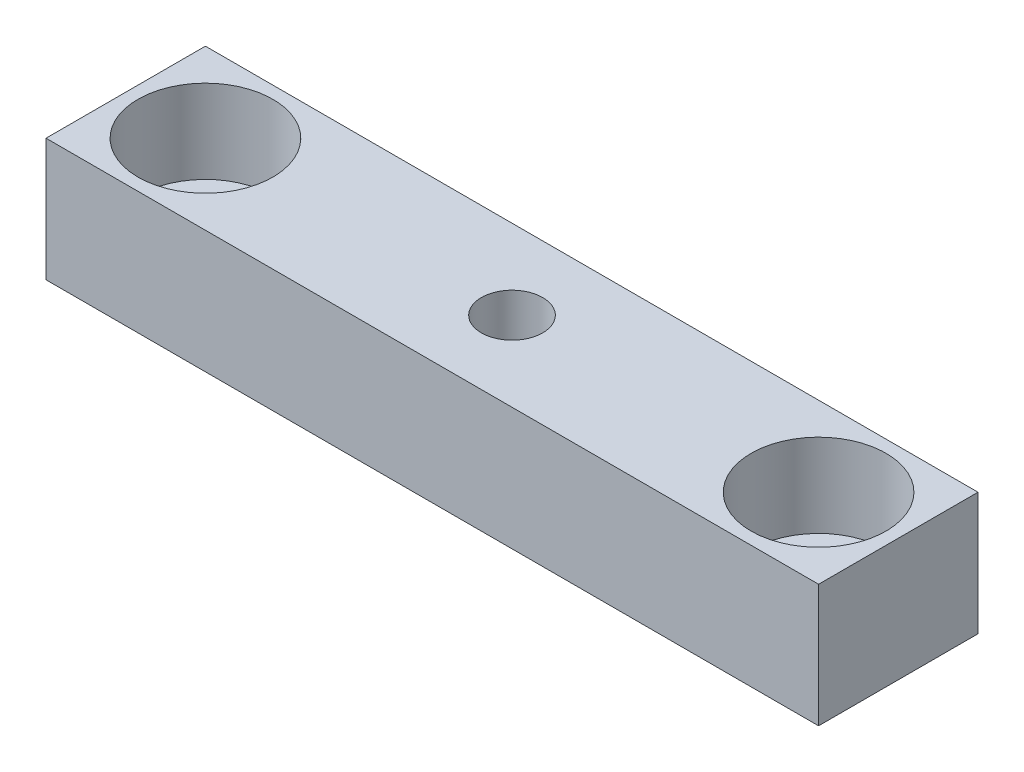
SolidWorks part; units mm, degrees
material "6061 合金"
ref_plane "前视基准面" through (0, 0, 0) normal (0, 0, 1) x (1, 0, 0)
ref_plane "上视基准面" through (0, 0, 0) normal (0, 1, 0) x (1, 0, 0)
ref_plane "右视基准面" through (0, 0, 0) normal (1, 0, 0) x (0, 0, -1)
sketch "草图1" plane through (0, 0, 0) normal (0, 1, 0) x (1, 0, 0)
  line L1 (-31.5, 6.5) -> (31.5, 6.5)
  line L2 (-31.5, 6.5) -> (-31.5, -6.5)
  line L3 (-31.5, -6.5) -> (31.5, -6.5)
  line L4 (31.5, 6.5) -> (31.5, -6.5)
  line L5 (-31.5, 6.5) -> (31.5, -6.5) construction
  line L6 (-31.5, -6.5) -> (31.5, 6.5) construction
  point P0 (0, 0)
extrude "凸台-拉伸1" add sketch "草图1" along normal blind 10
sketch "草图2" plane through (0, 10, 0) normal (0, 1, 0) x (1, 0, 0)
  line L0 (-25, 0) -> (25, 0) construction
  line L1 (-16.5, 0) -> (16.5, 0) construction
  point P6 (0, 0)
hole_wizard "打孔尺寸(%根据)内六角圆柱头螺钉的类型1" positions "3D草图1" profile "草图3" counterbore size "M6" standard "GB" end condition through all
sketch3d "3D草图1"
  point P0 (-25, 10, 0)
  point P3 (25, 10, 0)
sketch "草图3" plane through (-25, 10, 0) normal (1, 0, 0) x (0, 0, 1)
  line L0 (0, 0) -> (0, 10)
  line L1 (0, 10) -> (3.3, 10)
  line L3 (3.3, 10) -> (3.3, 6.8)
  line L4 (3.3, 6.8) -> (5.5, 6.8)
  line L5 (5.5, 6.8) -> (5.5, 0)
  line L7 (5.5, 0) -> (0, 0)
  line L11 (0, -6.35) -> (0, 107.95) construction
  dimension "通孔孔直径" = 6.6
  dimension "通孔孔深度" = 10
  dimension "柱形沉头孔直径" = 11
  dimension "柱形沉头孔深度" = 6.8
sketch "草图4" plane through (0, 0, 0) normal (0, -1, 0) x (1, 0, 0)
  line L0 (-25, 0) -> (-15, 0) construction
  line L1 (-25, 0) -> (25, 0) construction
  line L2 (25, 0) -> (15, 0) construction
  dimension "D1" = 10
  dimension "D2" = 10
hole_wizard "大小mm 暗销孔1" positions "3D草图2" profile "草图5" hole size "Ø4.0" standard "GB"
sketch3d "3D草图2"
  point P0 (-15, 0, 0)
sketch "草图5" plane through (-15, 0, 0) normal (1, 0, 0) x (0, 0, -1)
  line L0 (0, 0) -> (0, 6.2017)
  line L1 (0, 6.2017) -> (2, 5)
  line L2 (2, 5) -> (2, 0)
  line L5 (2, 0) -> (0, 0)
  line L10 (0, 6.2017) -> (-2, 5) construction
  line L11 (0, -6.35) -> (0, 107.95) construction
  dimension "孔直径" = 4
  dimension "孔深度" = 5
  dimension "导头角度" = 118
sketch "草图6" plane through (0, 0, 0) normal (0, -1, 0) x (1, 0, 0)
  line L0 (14.5, 0) -> (15.5, 0) construction
  line L1 (-25, 0) -> (25, 0) construction
  line L2 (14.5, 2) -> (15.5, 2)
  line L3 (14.5, -2) -> (15.5, -2)
  arc A0 (14.5, 2) -> (14.5, -2) centre (14.5, 0) ccw
  arc A1 (15.5, -2) -> (15.5, 2) centre (15.5, 0) ccw
  circle A2 centre (-15, 0) radius 2 construction
  point P5 (15, 0)
  dimension "D1" = 1
extrude "切除-拉伸1" cut sketch "草图6" against normal blind 5
fillet "圆角1" [suppressed] radius 2
sketch "草图7" plane through (0, 0, 0) normal (0, 1, 0) x (1, 0, 0)
  circle A0 centre (0, 0) radius 2
hole_wizard "M6 螺纹孔1" positions "3D草图3" profile "草图8" tap size "M6" standard "GB" end condition through all
sketch3d "3D草图3"
  circle A0 centre (0, 0, 0) radius 2 construction
  point P0 (0, 0, 0)
  point P3 (0, 0, 0)
  point P5 (0, 0, 0)
  point P11 (0, 2, 0)
sketch "草图8" plane through (0, 0, 0) normal (1, 0, 0) x (0, 0, -1)
  line L0 (0, 0) -> (0, 10)
  line L1 (0, 10) -> (2.5, 10)
  line L2 (2.5, 10) -> (2.5, 0)
  line L5 (2.5, 0) -> (0, 0)
  line L11 (0, -6.35) -> (0, 107.95) construction
  dimension "通孔螺纹孔钻头直径" = 5
  dimension "通孔螺纹孔钻头深度" = 10
cosmetic thread "孔螺蚊线3" parameters "D2"=6
